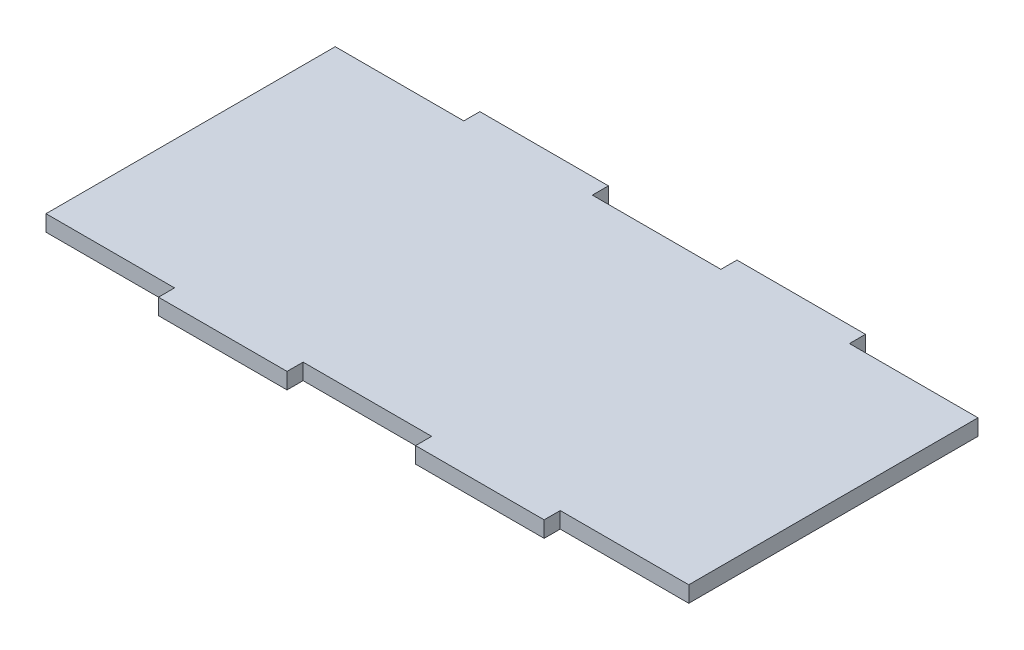
SolidWorks part; units mm, degrees
ref_plane "Front Plane" through (0, 0, 0) normal (0, 0, 1) x (1, 0, 0)
ref_plane "Top Plane" through (0, 0, 0) normal (0, 1, 0) x (1, 0, 0)
ref_plane "Right Plane" through (0, 0, 0) normal (1, 0, 0) x (0, 0, -1)
sketch "Sketch1" plane through (0, 0, 0) normal (0, 1, 0) x (1, 0, 0)
  line L0 (63.5, 57.15) -> (63.5, -72.6119) construction
  line L1 (0, 0) -> (25.4, 0)
  line L2 (0, 0) -> (0, 15.875)
  line L3 (0, 57.15) -> (25.4, 57.15)
  line L4 (127, 0) -> (127, 15.875)
  line L5 (50.8, 57.15) -> (50.8, 60.325)
  line L6 (50.8, 60.325) -> (25.4, 60.325)
  line L7 (25.4, 60.325) -> (25.4, 57.15)
  line L8 (50.8, 57.15) -> (76.2, 57.15)
  line L9 (0, 28.575) -> (127, 28.575) construction
  line L10 (76.2, 57.15) -> (76.2, 60.325)
  line L11 (76.2, 60.325) -> (101.6, 60.325)
  line L12 (101.6, 60.325) -> (101.6, 57.15)
  line L13 (50.8, -3.175) -> (25.4, -3.175)
  line L14 (25.4, -3.175) -> (25.4, 0)
  line L15 (50.8, 0) -> (50.8, -3.175)
  line L16 (76.2, 0) -> (76.2, -3.175)
  line L17 (76.2, -3.175) -> (101.6, -3.175)
  line L18 (101.6, -3.175) -> (101.6, 0)
  line L19 (101.6, 57.15) -> (127, 57.15)
  line L20 (101.6, 0) -> (127, 0)
  line L21 (50.8, 0) -> (76.2, 0)
  line L25 (0, 41.275) -> (0, 15.875)
  line L29 (0, 41.275) -> (0, 57.15)
  line L30 (127, 41.275) -> (127, 57.15)
  line L31 (127, 41.275) -> (127, 15.875)
  dimension "D1" = 57.15
  dimension "D2" = 127
  dimension "D3" = 3.175
  dimension "D4" = 25.4
  dimension "D5" = 12.7
extrude "Boss-Extrude1" add sketch "Sketch1" along normal blind 3.175
